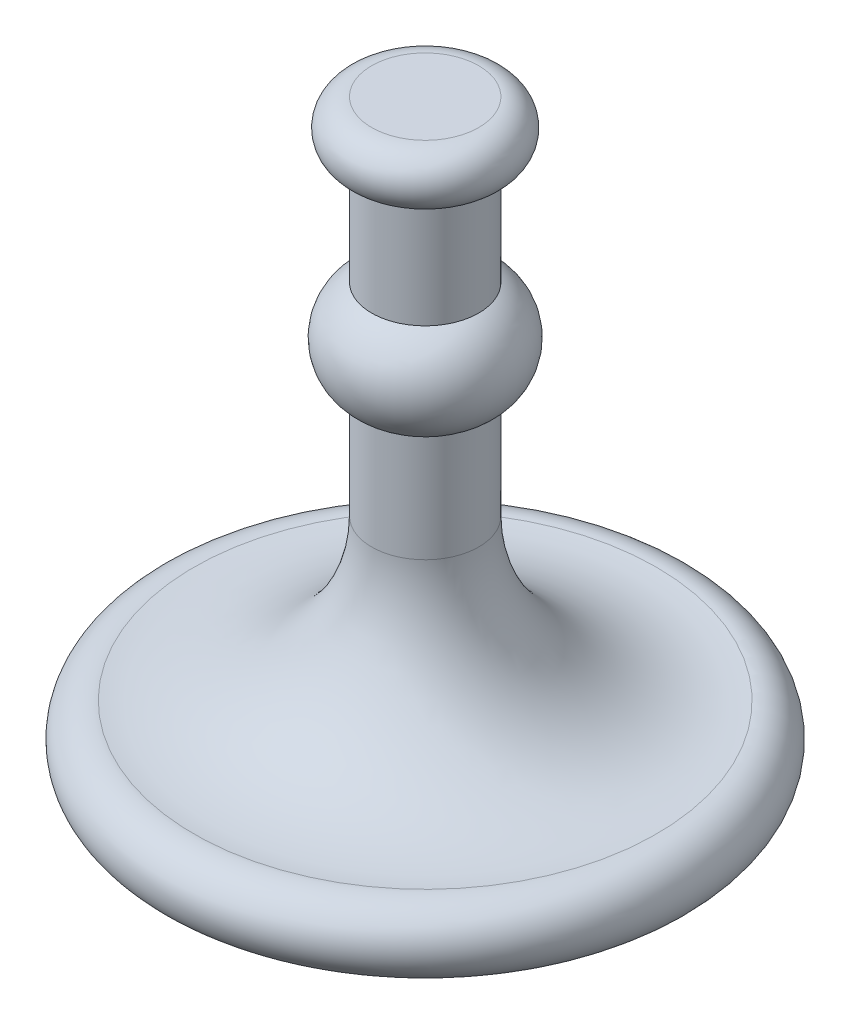
SolidWorks part; units mm, degrees
ref_plane "Front Plane" through (0, 0, 0) normal (0, 0, 1) x (1, 0, 0)
ref_plane "Top Plane" through (0, 0, 0) normal (0, 1, 0) x (1, 0, 0)
ref_plane "Right Plane" through (0, 0, 0) normal (1, 0, 0) x (0, 0, -1)
sketch "Sketch1" plane through (0, 0, 0) normal (0, 0, 1) x (1, 0, 0)
  line L0 (0, 0) -> (0, 220)
  line L1 (0, 220) -> (20, 220)
  line L2 (0, 0) -> (90, 0)
  line L3 (20, 200) -> (20, 160)
  line L4 (20, 124.3712) -> (20, 84.3712)
  arc A0 (20, 220) -> (20, 200) centre (20, 210) cw
  arc A1 (20, 160) -> (20, 124.3712) centre (10.9089, 142.1856) cw
  arc A2 (20, 84.3712) -> (86.3198, 24.705) centre (80, 84.3712) ccw
  arc A3 (86.3198, 24.705) -> (90, 0) centre (87.6364, 12.2745) cw
  point P14 (100, 14.1163)
  dimension "D4" = 10
  dimension "D5" = 20
  dimension "D7" = 60
  dimension "D9" = 12.5
  dimension "D1" = 220
  dimension "D2" = 20
  dimension "D3" = 90
  dimension "D6" = 40
  dimension "D8" = 80
revolve "Revolve1" add sketch "Sketch1" angle 360 about L0
sketch "Sketch2" plane through (0, 0, 0) normal (0, 0, 1) x (1, 0, 0)
  line L0 (0, 10) -> (60, 10)
  line L1 (0, 227.4356) -> (0, 175.1288) construction
  arc A0 (60, 10) -> (183.5921, 75) centre (60, 160) ccw
  arc A1 (183.5921, 75) -> (150.6342, 75) centre (167.1131, 86.3333) ccw
  ellipse E0 centre (0, 10) end of major axis (17.5, 10) minor radius 5
  dimension "D2" = 150
  dimension "D4" = 20
  dimension "D1" = 60
  dimension "D3" = 65
  dimension "D5" = 10
  dimension "D6" = 10
  dimension "D7" = 35
